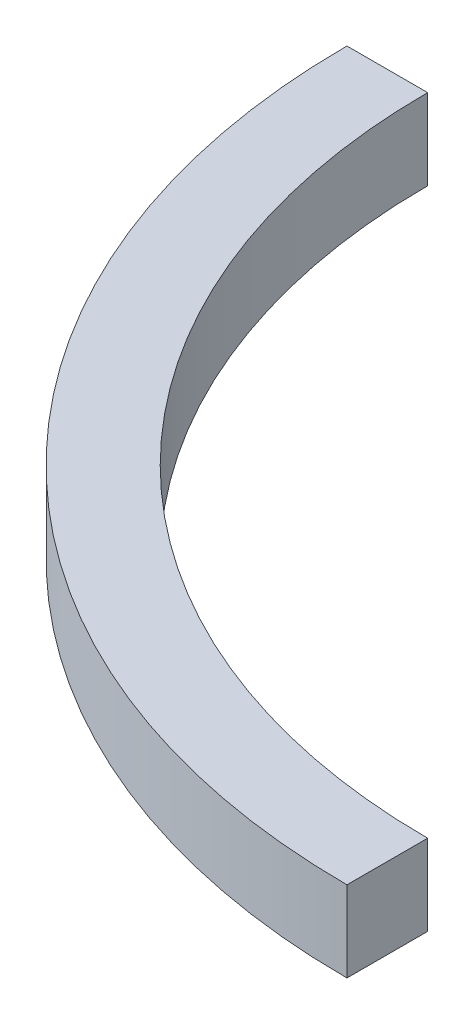
SolidWorks part; units mm, degrees
ref_plane "前基準面" through (0, 0, 0) normal (0, 0, 1) x (1, 0, 0)
ref_plane "上基準面" through (0, 0, 0) normal (0, 1, 0) x (1, 0, 0)
ref_plane "右基準面" through (0, 0, 0) normal (1, 0, 0) x (0, 0, -1)
sketch "草圖1" plane through (0, 0, 0) normal (0, 1, 0) x (1, 0, 0)
  line L0 (0, -55) -> (0, 55) construction
  line L1 (-27, 0) -> (-24, 0)
  line L2 (0, -24) -> (0, -27)
  line L3 (-55, 0) -> (55, 0) construction
  arc A0 (0, -27) -> (-27, 0) centre (0, 0) cw
  arc A1 (0, -24) -> (-24, 0) centre (0, 0) cw
  point P8 (0, 0)
  point P11 (0, 0)
  dimension "D1" = 27
  dimension "D2" = 24
extrude "填料-伸長1" add sketch "草圖1" along normal blind 3
